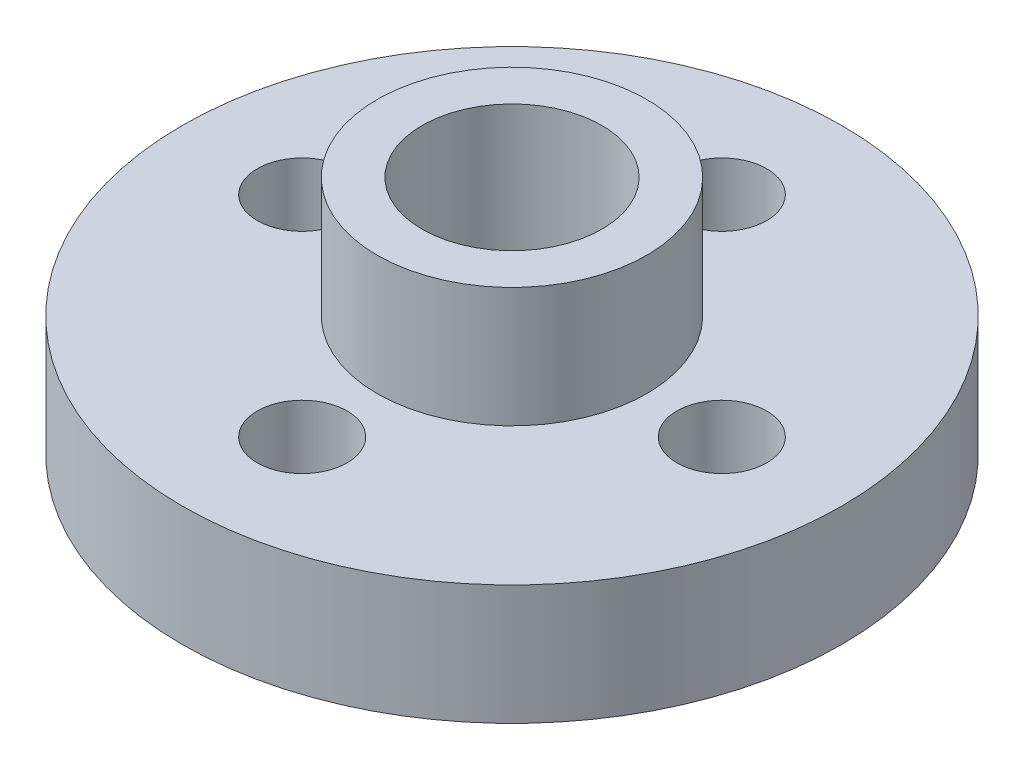
SolidWorks part; units mm, degrees
ref_plane "Front Plane" through (0, 0, 0) normal (0, 0, 1) x (1, 0, 0)
ref_plane "Top Plane" through (0, 0, 0) normal (0, 1, 0) x (1, 0, 0)
ref_plane "Right Plane" through (0, 0, 0) normal (1, 0, 0) x (0, 0, -1)
sketch "Sketch1" plane through (0, 0, 0) normal (0, 1, 0) x (1, 0, 0)
  circle A0 centre (0, 0) radius 11
  dimension "10" = 22
extrude "Boss-Extrude2" add sketch "Sketch1" along normal blind 8
sketch "Sketch3" plane through (0, 8, 0) normal (0, 1, 0) x (1, 0, 0)
  line L0 (-3, 0) -> (-11, 0) construction
  line L1 (0, 3) -> (0, 11) construction
  line L2 (0, -3) -> (0, -11) construction
  line L3 (3, 0) -> (11, 0) construction
  circle A0 centre (0, 0) radius 3
  circle A1 centre (0, 0) radius 11 construction
  circle A2 centre (-7, 0) radius 1.5
  circle A3 centre (0, 7) radius 1.5
  circle A4 centre (7, 0) radius 1.5
  circle A5 centre (0, -7) radius 1.5
  dimension "D1" = 6
  dimension "D2" = 3
  dimension "D3" = 3
  dimension "D4" = 3
  dimension "D5" = 3
extrude "Cut-Extrude2" cut sketch "Sketch3" against normal blind 12
sketch "Sketch4" plane through (0, 8, 0) normal (0, 1, 0) x (1, 0, 0)
  circle A0 centre (0, 0) radius 4.5
  circle A1 centre (0, 0) radius 11
  dimension "D1" = 9
extrude "Cut-Extrude3" cut sketch "Sketch4" against normal blind 4
